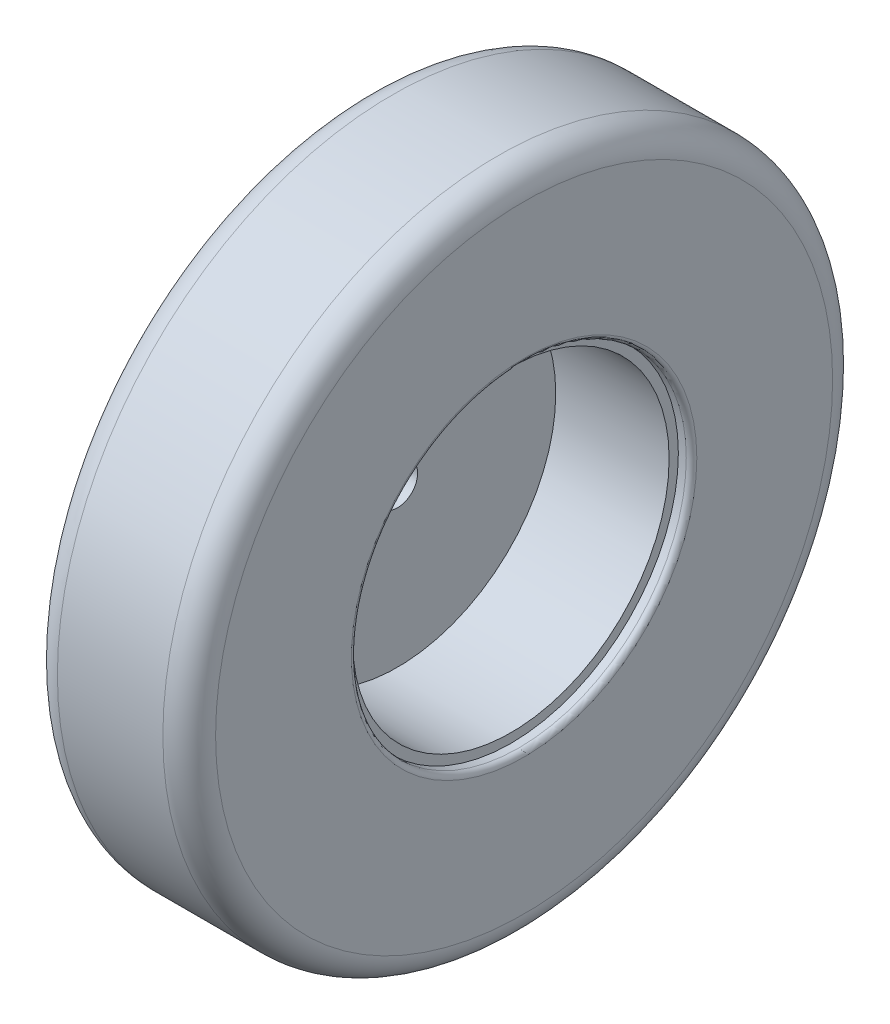
SolidWorks part; units mm, degrees
other "LHS Wheel" parameters "D1"=13.6453, "D2"=113.5139, "D3"=155.7266, "D4"=155.7266
ref_plane "Front Plane" through (0, 0, 0) normal (0, 0, 1) x (1, 0, 0)
ref_plane "Top Plane" through (0, 0, 0) normal (0, 1, 0) x (1, 0, 0)
ref_plane "Right Plane" through (0, 0, 0) normal (1, 0, 0) x (0, 0, -1)
sketch "Sketch1" plane through (0, 0, 0) normal (1, 0, 0) x (0, 0, -1)
  circle A1 centre (0, 0) radius 7.625
  circle A2 centre (0, 0) radius 63.5
  dimension "D1" = 15.25
  dimension "D3" = 127
extrude "Hub Face" add sketch "Sketch1" along normal blind 7 from offset 5
sketch "Sketch2" plane through (0, 0, 0) normal (1, 0, 0) x (0, 0, -1)
  circle A0 centre (0, 0) radius 63.5
  circle A1 centre (0, 0) radius 60
  dimension "D1" = 127
  dimension "D2" = 120
extrude "Hub" add sketch "Sketch2" along normal blind 50 from offset 5
sketch "Sketch3" plane through (0, 0, 0) normal (1, 0, 0) x (0, 0, -1)
  circle A0 centre (0, 0) radius 127
  circle A1 centre (0, 0) radius 63.5
  dimension "D1" = 254
  dimension "D2" = 127
extrude "Rubber" add sketch "Sketch3" along normal blind 60
fillet "Fillet1" radius 10 2 edges at (0, 0, -127) (60, 0, -127)
fillet "Fillet2" radius 2 2 edges at (60, 0, -63.5) (0, 0, -63.5)
mirror "Mirror1" [suppressed] about plane through (0, 0, 0) normal (1, 0, 0)
equation "\"tireWidth\"= 60mm"
equation "\"tireDiameter\"= 10in"
equation "\"shaftDiameter\"= 15mm"
equation "\"hubDiameter\"= 5in"
equation "\"D1@Sketch1\"=\"shaftDiameter\" + 0.25mm"
equation "\"hubMaterialThickness\"= 7mm"
equation "\"D1@Hub Face\" = \"hubMaterialThickness\""
equation "\"D3@Sketch1\"=\"hubDiameter\""
equation "\"D1@Sketch2\"=\"hubDiameter\""
equation "\"D2@Sketch2\"=\"hubDiameter\"-\"hubMaterialThickness\""
equation "\"D1@Hub\"=\"hubWidth\""
equation "\"D1@Sketch3\"=\"tireDiameter\""
equation "\"D2@Sketch3\"=\"hubDiameter\""
equation "\"D1@Rubber\" = \"tireWidth\""
equation "\"hubWidth\"= 50mm"
equation "\"D19@Hub\"=(\"tireWidth\"-\"hubWidth\")/2"
equation "\"D19@Hub Face\"=(\"tireWidth\"-\"hubWidth\")/2"
